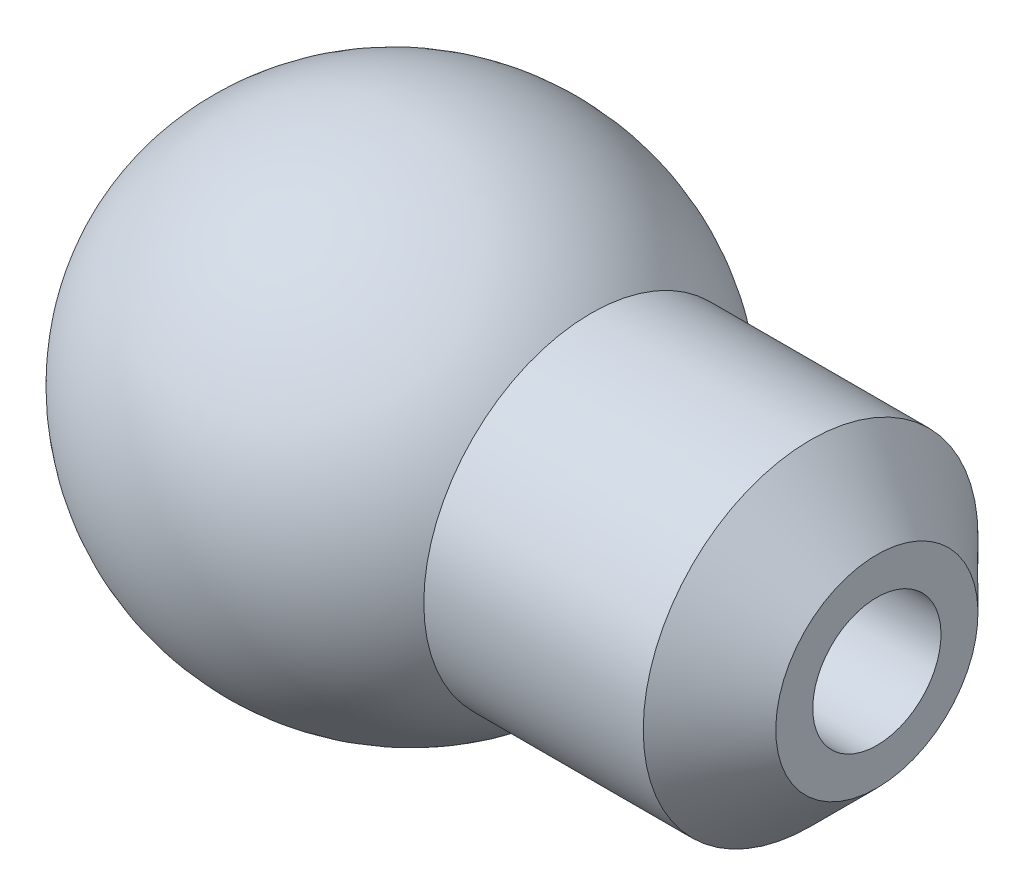
SolidWorks part; units mm, degrees
ref_plane "Front Plane" through (0, 0, 0) normal (0, 0, 1) x (1, 0, 0)
ref_plane "Top Plane" through (0, 0, 0) normal (0, 1, 0) x (1, 0, 0)
ref_plane "Right Plane" through (0, 0, 0) normal (1, 0, 0) x (0, 0, -1)
sketch "Sketch1" plane through (0, 0, 0) normal (0, 0, 1) x (1, 0, 0)
  line L2 (0, 26) -> (60, 26)
  line L4 (60, 26) -> (60, 41)
  line L6 (60, 41) -> (33.1299, 67.8701)
  line L7 (33.1299, 67.8701) -> (-55.8501, 67.8701)
  line L11 (-240, 0) -> (48.5019, 0) construction
  line L22 (0, 26) -> (0, 0)
  line L24 (0, 0) -> (-240, 0)
  arc A7 (-240, 0) -> (-55.8501, 67.8701) centre (-132.4482, -8.0579) cw
  dimension "D12" = 240
  dimension "D1" = 26
  dimension "D3" = 60
  dimension "D4" = 15
  dimension "D6" = 135
  dimension "D7" = 38
  dimension "D15" = 88.98
revolve "Revolve1" add sketch "Sketch1" angle 360 about L11
sketch "Sketch3" plane through (0, 0, 0) normal (1, 0, 0) x (0, 0, -1)
  line L0 (0, 26) -> (0, -26)
  arc A0 (0, 26) -> (0, -26) centre (0, 0) cw
  circle A1 centre (0, 0) radius 26 construction
sketch "Sketch6" plane through (0, 0, 0) normal (0, 0, 1) x (1, 0, 0)
  line L0 (-247.9718, 0) -> (72.1755, 0) construction
  line L1 (-56.3341, 76.4415) -> (-56.3341, -91.2652) construction
  line L2 (-240, 0) -> (-240, 110.6683) construction
  line L3 (-240, 110.6683) -> (-240, -148.8151) construction
  line L4 (60, 0) -> (60, -27.0892)
  line L5 (60, -41) -> (60, 41) construction
  line L6 (60, -26) -> (60, 26) construction
  line L7 (60, -27.0892) -> (57.533, -27.0892)
  line L8 (57.533, -27.0892) -> (57.533, -42.0892)
  line L9 (57.533, -42.0892) -> (33.1299, -66.4923)
  line L10 (33.1299, -67.8701) -> (33.1299, 67.8701) construction
  line L11 (33.1299, -66.4923) -> (-56.3341, -66.4923)
  line L12 (60, 0) -> (60, 24.9108)
  line L13 (60, 24.9108) -> (57.533, 24.9108)
  line L14 (57.533, 24.9108) -> (57.533, 40.4037)
  line L15 (57.533, 40.4037) -> (33.1299, 65.972)
  line L16 (33.1299, 65.972) -> (-56.3341, 65.972)
  line L17 (60, 0) -> (-240, 0)
  line L18 (-56.3341, 65.972) -> (-56.3341, -66.4923)
  line L19 (-238, 110.6683) -> (-238, -148.8151) construction
  line L20 (-238, 110.6683) -> (-238, -148.8151)
  point P27 (0, 0)
  point P28 (0, 0)
  point P29 (0, 0)
  point P30 (0, 0)
  point P31 (33.1299, 65.972)
  point P32 (0, 0)
  point P33 (0, 0)
  point P34 (0, 0)
  point P35 (0, 0)
  point P36 (0, 0)
  point P37 (0, 0)
  point P38 (0, 0)
  point P39 (0, 0)
  dimension "D1" = 2
